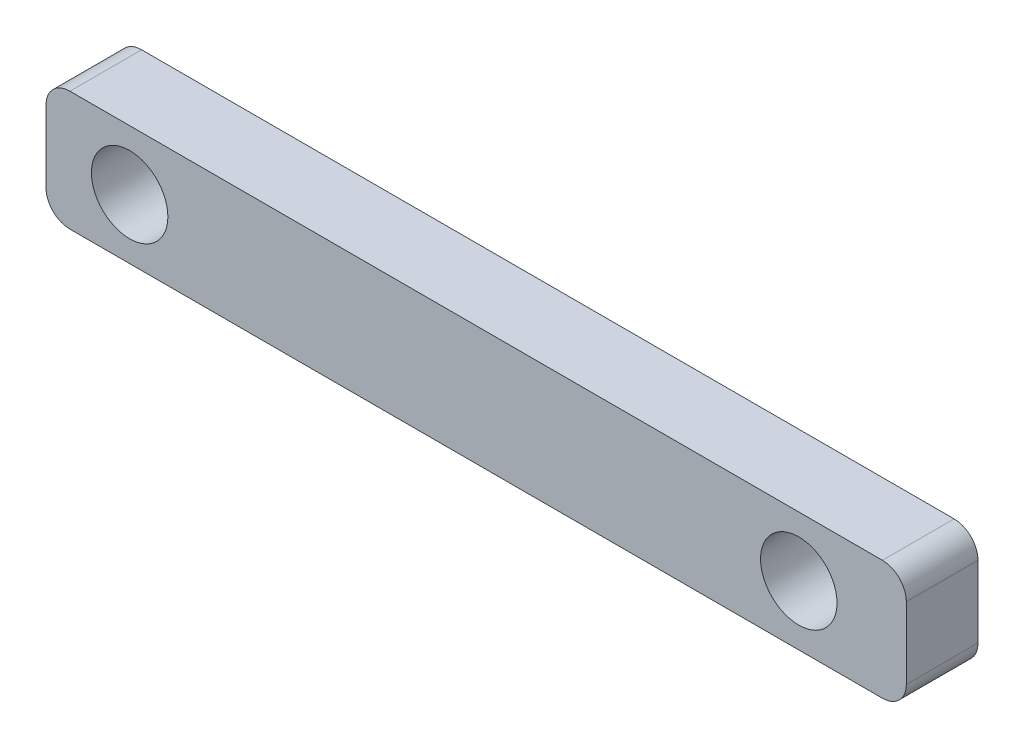
SolidWorks part; units mm, degrees
ref_plane "前基準面" through (0, 0, 0) normal (0, 0, 1) x (1, 0, 0)
ref_plane "上基準面" through (0, 0, 0) normal (0, 1, 0) x (1, 0, 0)
ref_plane "右基準面" through (0, 0, 0) normal (1, 0, 0) x (0, 0, -1)
sketch "草圖1" plane through (0, 0, 0) normal (0, 0, 1) x (1, 0, 0)
  line L1 (12.8251, -7.3855) -> (46.8251, -7.3855)
  line L2 (11.8251, -8.3855) -> (11.8251, -11.3855)
  line L3 (12.8251, -12.3855) -> (46.8251, -12.3855)
  line L4 (47.8251, -8.3855) -> (47.8251, -11.3855)
  circle A0 centre (15.3251, -9.8855) radius 1.6
  circle A1 centre (43.3251, -9.8855) radius 1.6
  arc A2 (46.8251, -12.3855) -> (47.8251, -11.3855) centre (46.8251, -11.3855) ccw
  arc A3 (47.8251, -8.3855) -> (46.8251, -7.3855) centre (46.8251, -8.3855) ccw
  arc A4 (12.8251, -12.3855) -> (11.8251, -11.3855) centre (12.8251, -11.3855) cw
  arc A5 (11.8251, -8.3855) -> (12.8251, -7.3855) centre (12.8251, -8.3855) cw
  point P8 (0, 0)
  point P9 (0, 0)
  point P10 (-269.0696, 18.8501)
  point P13 (47.8251, -12.3855)
  point P16 (47.8251, -7.3855)
  point P21 (11.8251, -7.3855)
  dimension "D1" = 3.2
  dimension "D2" = 3.2
  dimension "D8" = 1
  dimension "D3" = 28
  dimension "D4" = 5
  dimension "D5" = 36
  dimension "D6" = 3.5
  dimension "D7" = 2.5
extrude "填料-伸長1" add sketch "草圖1" along normal blind 3
